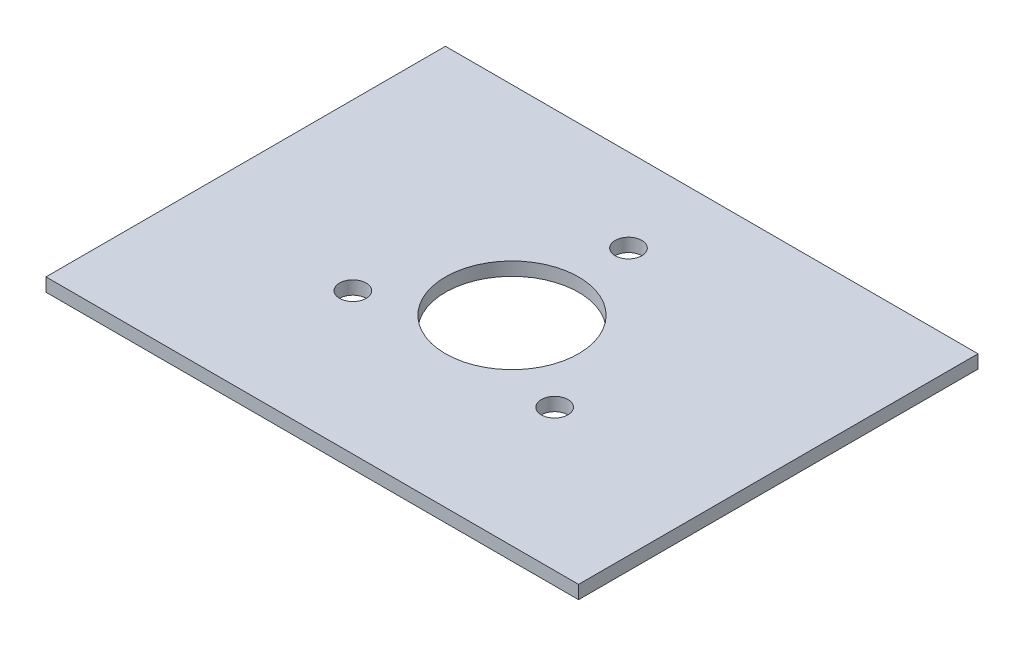
SolidWorks part; units mm, degrees
ref_plane "Plan de face" through (0, 0, 0) normal (0, 0, 1) x (1, 0, 0)
ref_plane "Plan de dessus" through (0, 0, 0) normal (0, 1, 0) x (1, 0, 0)
ref_plane "Plan de droite" through (0, 0, 0) normal (1, 0, 0) x (0, 0, -1)
sketch "Esquisse1" plane through (0, 0, 0) normal (0, 1, 0) x (1, 0, 0)
  line L0 (0, 0) -> (40, 0) construction
  line L1 (-40, -30) -> (40, -30)
  line L2 (-40, -30) -> (-40, 30)
  line L3 (-40, 30) -> (40, 30)
  line L4 (40, -30) -> (40, 30)
  line L5 (-40, -30) -> (40, 30) construction
  line L6 (-40, 30) -> (40, -30) construction
  line L7 (0, 0) -> (15.1554, -8.75) construction
  circle A0 centre (15.1554, -8.75) radius 2
  circle A1 centre (-15.1554, -8.75) radius 2
  circle A2 centre (0, 17.5) radius 2
  circle A3 centre (0, 0) radius 10
  point P0 (0, 0)
  point P16 (0, 0)
  dimension "D3" = 4
  dimension "D7" = 20
  dimension "D1" = 60
  dimension "D2" = 80
  dimension "D4" = 30
  dimension "D5" = 17.5
  dimension "D6" = 3
extrude "Boss.-Extru.1" add sketch "Esquisse1" along normal blind 2
